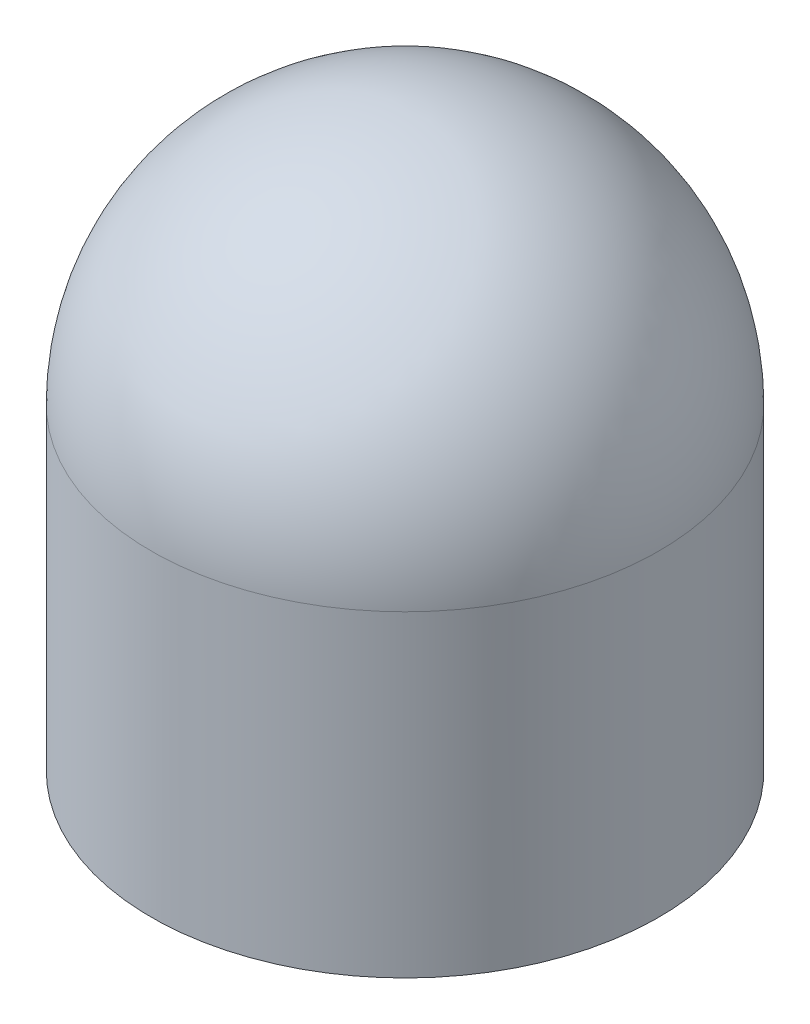
SolidWorks part; units mm, degrees
material "Caucho natural"
ref_plane "Alzado" through (0, 0, 0) normal (0, 0, 1) x (1, 0, 0)
ref_plane "Planta" through (0, 0, 0) normal (0, 1, 0) x (1, 0, 0)
ref_plane "Vista lateral" through (0, 0, 0) normal (1, 0, 0) x (0, 0, -1)
sketch "Croquis1" plane through (0, 0, 0) normal (0, 0, 1) x (1, 0, 0)
  line L0 (0, 0) -> (0, 8.2225) construction
  line L1 (0, 0) -> (-10, 0)
  line L2 (-10, 0) -> (-10, -0.0903)
  line L7 (0, 0) -> (0, 12.5) construction
  line L8 (10, 0) -> (10, -0.0903) construction
  line L9 (0, 0) -> (10, 0) construction
  line L10 (-10, 0) -> (-10, 12.5)
  line L11 (0, 0) -> (0, 22.5)
  arc A1 (0, 22.5) -> (-10, 12.5) centre (0, 12.5) ccw
  point P12 (0, 8.2225)
  dimension "D2" = 12.5
  dimension "D1" = 20
revolve "Revolución2" add sketch "Croquis1" angle 360 about L0
sketch "Croquis2" plane through (0, 0, 0) normal (0, -1, 0) x (1, 0, 0)
  circle A0 centre (0, 0) radius 5
  dimension "D1" = 10
extrude "Cortar-Extruir1" cut sketch "Croquis2" against normal blind 12.5
